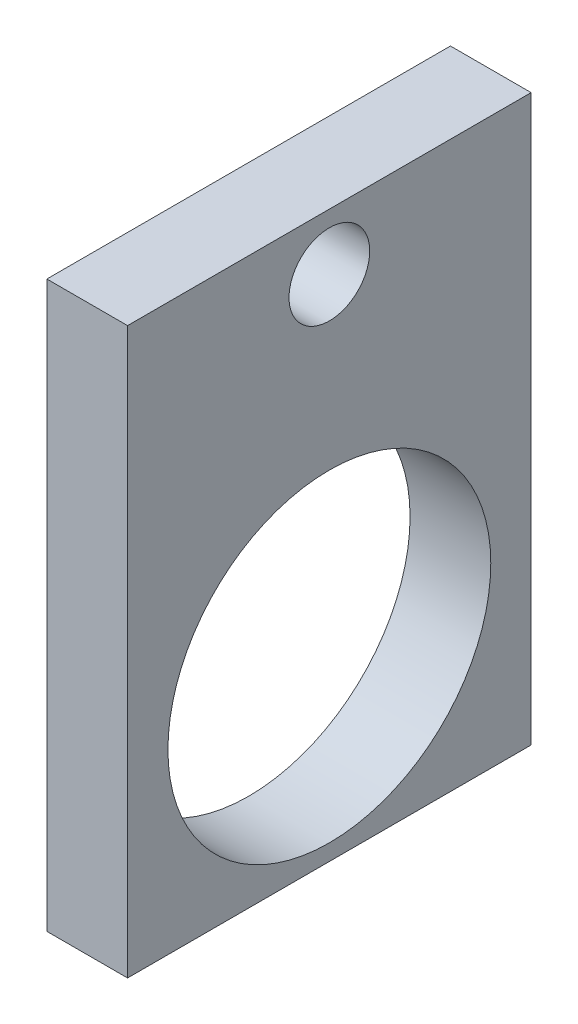
SolidWorks part; units mm, degrees
ref_plane "Front Plane" through (0, 0, 0) normal (0, 0, 1) x (1, 0, 0)
ref_plane "Top Plane" through (0, 0, 0) normal (0, 1, 0) x (1, 0, 0)
ref_plane "Right Plane" through (0, 0, 0) normal (1, 0, 0) x (0, 0, -1)
sketch "Sketch1" plane through (0, 0, 0) normal (1, 0, 0) x (0, 0, -1)
  line L0 (0, 32.9948) -> (0, -34.7617) construction
  line L1 (-15.875, 22.225) -> (15.875, 22.225)
  line L2 (-15.875, 22.225) -> (-15.875, -22.225)
  line L3 (-15.875, -22.225) -> (15.875, -22.225)
  line L4 (15.875, 22.225) -> (15.875, -22.225)
  line L5 (-15.875, 22.225) -> (15.875, -22.225) construction
  line L6 (-15.875, -22.225) -> (15.875, 22.225) construction
  line L7 (0, 22.225) -> (0, 20.955)
  line L8 (0, -20.955) -> (0, -22.225)
  circle A0 centre (0, -8.255) radius 12.7
  circle A1 centre (0, 17.78) radius 3.175
  point P0 (0, 0)
  dimension "D1" = 25.4
  dimension "D2" = 6.35
  dimension "D3" = 44.45
  dimension "D4" = 31.75
  dimension "D5" = 1.27
extrude "Boss-Extrude1" add sketch "Sketch1" along normal blind 6.35
